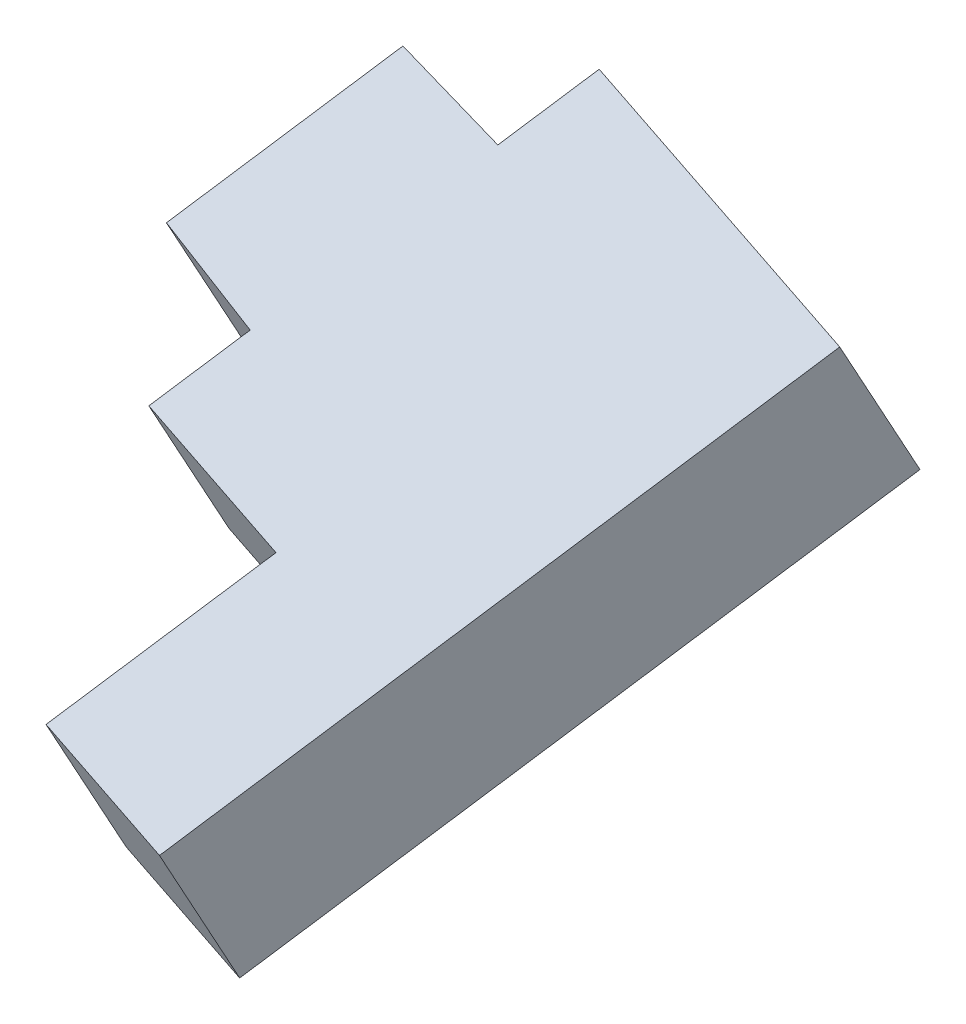
SolidWorks part; units mm, degrees
ref_plane "Front Plane" through (0, 0, 0) normal (0, 0, 1) x (1, 0, 0)
ref_plane "Top Plane" through (0, 0, 0) normal (0, 1, 0) x (1, 0, 0)
ref_plane "Right Plane" through (0, 0, 0) normal (1, 0, 0) x (0, 0, -1)
ref_plane "Plane1" through (-30.2839, 190.5651, 90.8517) normal (-0.142, 0.8935, 0.426) x (0.9896, 0.1388, 0.0388)
sketch "Sketch1" plane through (-30.2839, 190.5651, 90.8517) normal (-0.142, 0.8935, 0.426) x (0.9896, 0.1388, 0.0388)
  line L0 (22.1624, 253.4449) -> (-4.2283, 172.2229) construction
  line L1 (22.1624, 253.4449) -> (-4.2283, 172.2229) construction
  line L2 (1.5977, 170.7372) -> (2.9282, 174.8318) construction
  line L3 (1.5977, 170.7372) -> (2.9282, 174.8318) construction
  line L4 (6.325, 177.0665) -> (8.9956, 185.2858)
  line L5 (8.9956, 185.2858) -> (0.8736, 187.9248)
  line L6 (0.8736, 187.9248) -> (2.051, 191.5484)
  line L7 (2.051, 191.5484) -> (-3.5906, 193.6018)
  line L8 (-3.5906, 193.6018) -> (-0.8435, 202.0566)
  line L9 (-0.8435, 202.0566) -> (4.9276, 200.4018)
  line L10 (4.9276, 200.4018) -> (6.105, 204.0253)
  line L11 (6.105, 204.0253) -> (21.474, 199.0316)
  line L12 (21.474, 199.0316) -> (13.572, 174.7118)
  line L13 (13.572, 174.7118) -> (6.325, 177.0665)
  line L14 (-9.9346, 174.077) -> (16.4561, 255.299) construction
  line L15 (-1.4811, 180.6778) -> (4.2252, 178.8237) construction
  line L16 (3.0479, 175.2002) -> (4.2252, 178.8237) construction
  dimension "D1" = 92
  dimension "D2" = 8.89
  dimension "D3" = 7.62
  dimension "D4" = 3.175
  dimension "D5" = 2.54
  dimension "D6" = 7.62
  dimension "D7" = 3.81
extrude "Boss-Extrude1" add sketch "Sketch1" along normal mid plane 6
